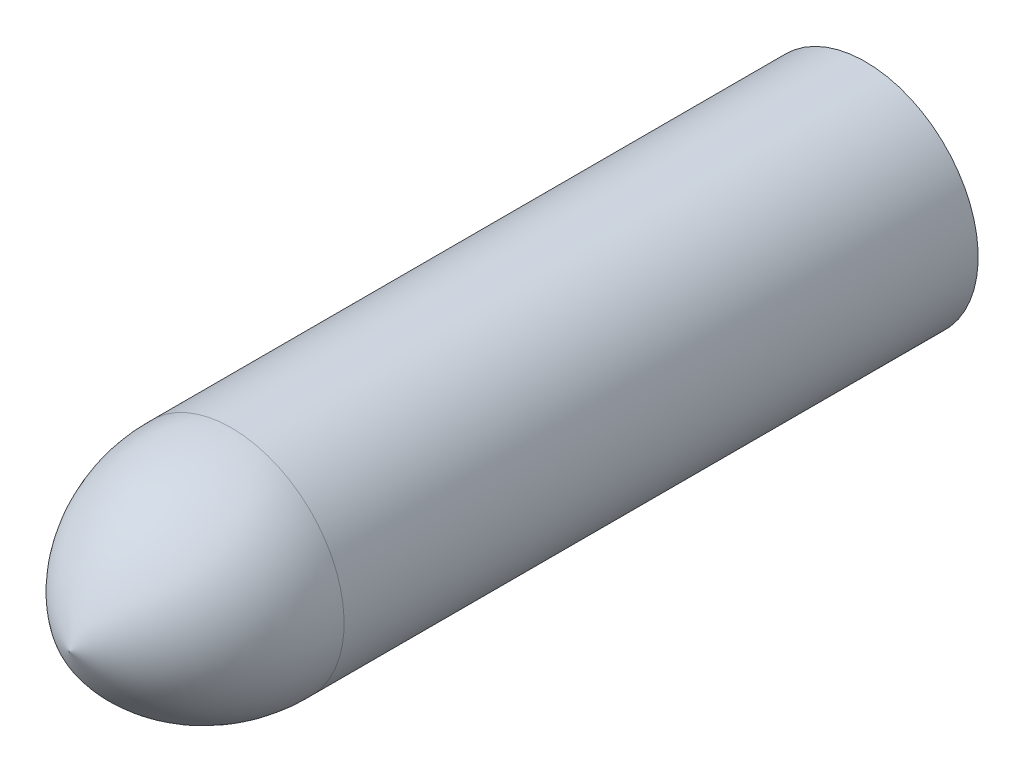
SolidWorks part; units mm, degrees
material "Plain Carbon Steel"
ref_plane "Front Plane" through (0, 0, 0) normal (0, 0, 1) x (1, 0, 0)
ref_plane "Top Plane" through (0, 0, 0) normal (0, 1, 0) x (1, 0, 0)
ref_plane "Right Plane" through (0, 0, 0) normal (1, 0, 0) x (0, 0, -1)
sketch "Sketch1" plane through (0, 0, 0) normal (0, 0, 1) x (1, 0, 0)
  circle A0 centre (0, 0) radius 32
  dimension "D1" = 64
extrude "Boss-Extrude1" add sketch "Sketch1" along normal blind 180
sketch "Sketch2" plane through (0, 0, 0) normal (1, 0, 0) x (0, 0, -1)
  line L0 (-180, 0) -> (-226, 0)
  line L1 (-180, 32) -> (-180, -32) construction
  line L2 (-180, 0) -> (-180, -32)
  arc A0 (-226, 0) -> (-180, -32) centre (-180.7431, 15.9942) ccw
  dimension "D2" = 48
  dimension "D1" = 46
revolve "Revolve1" add sketch "Sketch2" angle 360 about L0
